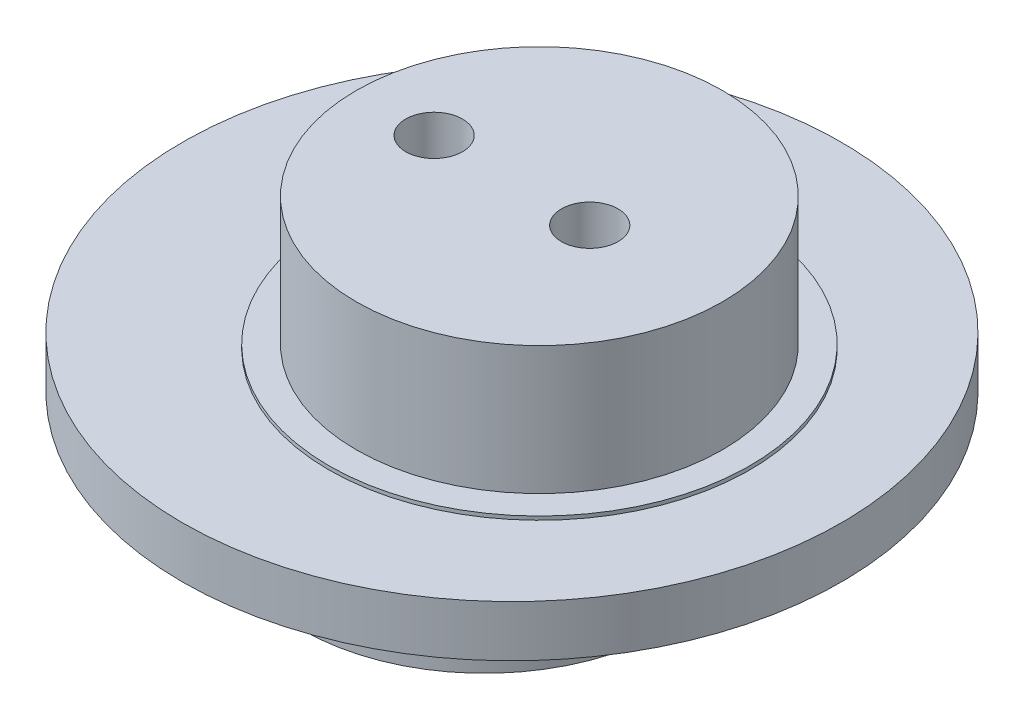
SolidWorks part; units mm, degrees
ref_plane "Ebene vorne" through (0, 0, 0) normal (0, 0, 1) x (1, 0, 0)
ref_plane "Ebene oben" through (0, 0, 0) normal (0, 1, 0) x (1, 0, 0)
ref_plane "Ebene rechts" through (0, 0, 0) normal (1, 0, 0) x (0, 0, -1)
sketch "Skizze1" plane through (0, 0, 0) normal (0, 1, 0) x (1, 0, 0)
  circle A0 centre (0, 0) radius 18
  dimension "D1" = 36
extrude "Aufsatz-Linear austragen1" add sketch "Skizze1" along normal blind 2.8
sketch "Skizze2" plane through (0, 2.8, 0) normal (0, 1, 0) x (1, 0, 0)
  line L0 (0, 0) -> (-50000, 0) construction
  circle A1 centre (1.5, 0) radius 11.5
  dimension "D1" = 1.5
  dimension "D2" = 23
extrude "Aufsatz-Linear austragen2" add sketch "Skizze2" along normal blind 0.2
sketch "Skizze3" plane through (0, 3, 0) normal (0, 1, 0) x (1, 0, 0)
  circle A0 centre (1.5, 0) radius 10
  dimension "D1" = 20
extrude "Aufsatz-Linear austragen3" add sketch "Skizze3" along normal blind 7
sketch "Skizze4" plane through (0, 0, 0) normal (0, -1, 0) x (1, 0, 0)
  line L0 (0, 0) -> (-50000, 0) construction
  circle A0 centre (-1.5, 0) radius 10
  dimension "D1" = 20
  dimension "D2" = 1.5
extrude "Aufsatz-Linear austragen4" add sketch "Skizze4" along normal blind 7
hole_wizard "Ø3.1 (3.1) Durchmesser Bohrung1" positions "Skizze5" profile "Skizze6" hole size "Ø3.1" standard "ISO" end condition through all
sketch "Skizze5" plane through (0, 10, 0) normal (0, 1, 0) x (1, 0, 0)
  line L0 (0, 0) -> (-50000, 0) construction
  line L1 (0, 0) -> (0, -50000) construction
  point P0 (4.25, 0)
  point P2 (-4.25, 0)
  dimension "D1" = 8.5
sketch "Skizze6" plane through (4.25, 10, 0) normal (1, 0, 0) x (0, 0, 1)
  line L0 (0, 0) -> (0, 17)
  line L1 (0, 17) -> (1.55, 17)
  line L2 (1.55, 17) -> (1.55, 0)
  line L5 (1.55, 0) -> (0, 0)
  line L11 (0, -6.35) -> (0, 107.95) construction
  dimension "Bohrerdurchmesser" = 3.1
  dimension "Bohrungstiefe" = 17
